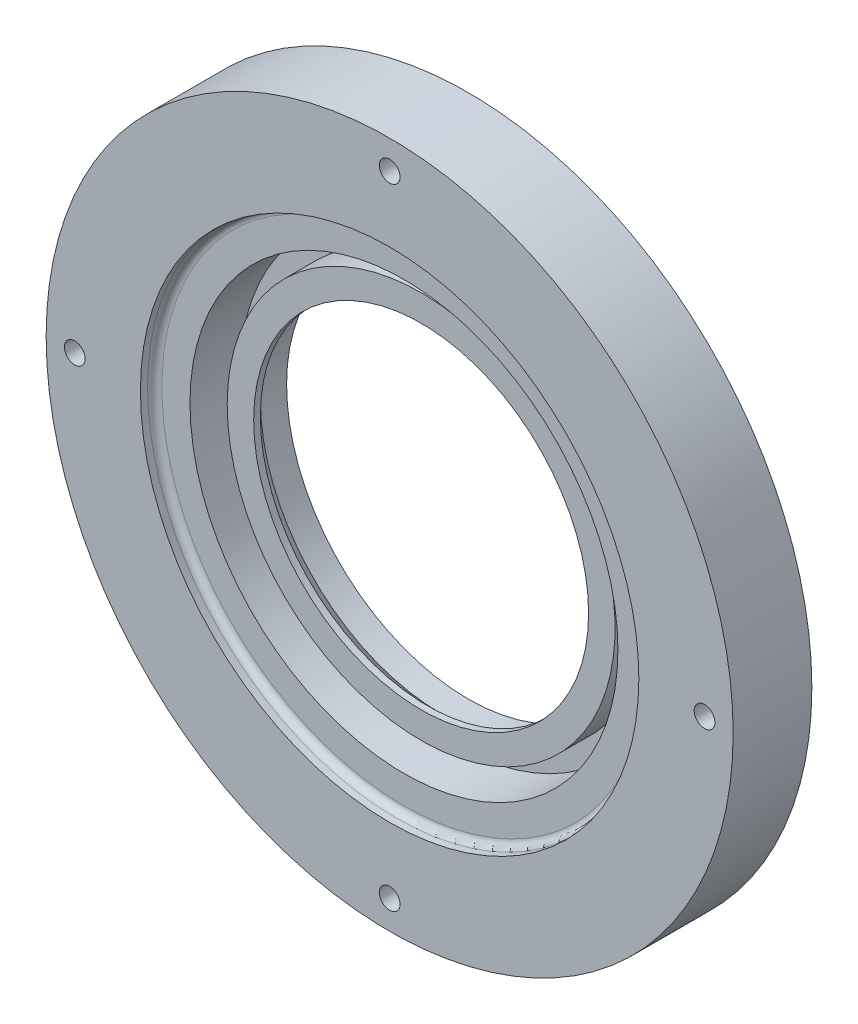
SolidWorks part; units mm, degrees
ref_plane "Front Plane" through (0, 0, 0) normal (0, 0, 1) x (1, 0, 0)
ref_plane "Top Plane" through (0, 0, 0) normal (0, 1, 0) x (1, 0, 0)
ref_plane "Right Plane" through (0, 0, 0) normal (1, 0, 0) x (0, 0, -1)
sketch "Sketch2" plane through (149.1164, 233.0393, -142.5293) normal (-0.6045, 0.7966, 0) x (0.7966, 0.6045, 0)
  line L0 (-23.4, 2.4) -> (-23.4, 3.3343)
  line L1 (-23.4, 3.3343) -> (-25.4, 5.3343)
  line L2 (-25.4, 5.3343) -> (-25.4, 9)
  line L3 (-25.4, 9) -> (-48, 9)
  line L17 (-27.1, 2.4) -> (-23.4, 2.4)
  line L18 (-34.825, 0) -> (-29.9, 0)
  line L19 (-23, 3.5) -> (-23, 2) construction
  line L20 (-29.9, 0) -> (-29.9, 7)
  line L21 (-29.5, 6.6) -> (-29.5, 0) construction
  line L25 (-25, 15) -> (-25, 5.5) construction
  line L26 (-25, 5.5) -> (-23, 3.5) construction
  line L27 (-27.1, 7) -> (-27.1, 2.4)
  line L28 (-27.5, 6.6) -> (-27.5, 2) construction
  line L30 (-27.1, 7) -> (-29.9, 7)
  line L32 (27.5, 2) -> (-27.5, 2) construction
  line L34 (29.5, 6.6) -> (-29.5, 6.6) construction
  line L36 (-29.5, 0) -> (29.5, 0) construction
  line L38 (-48, -2) -> (-34.825, -2)
  line L39 (-34.825, -2) -> (-34.825, 0)
  line L40 (-48, 9) -> (-48, -2)
  point P6 (-34.825, -1)
  dimension "D2" = 0.4
  dimension "D3" = 0.4
  dimension "D4" = 0.4
  dimension "D5" = 0.4
  dimension "D6" = 0.4
  dimension "D7" = 9
  dimension "D8" = 0.4
  dimension "D9" = 0.4
  dimension "D10" = 34.825
  dimension "D11" = 2
  dimension "D12" = 48
sketch "Sketch3" plane through (149.1164, 233.0393, -142.5293) normal (-0.6045, 0.7966, 0) x (0.7966, 0.6045, 0)
  line L0 (0, 13.4407) -> (0, -7.4209) construction
revolve "Revolve1" add sketch "Sketch2" angle 360 about L0
fillet "Fillet1" radius 1 1 edges at (114.2914, 233.0393, -142.5293)
hole_wizard "CBORE for M2.5 SHCS1" positions "Sketch10" profile "Sketch11" counterbore size "M2.5" standard "ANSI Metric"
sketch "Sketch10" plane through (0, 0, -151.5293) normal (0, 0, -1) x (-1, 0, 0)
  point P0 (-149.1164, 277.0393)
  point P2 (-149.1164, 189.0393)
  point P4 (-105.1164, 233.0393)
  point P6 (-193.1164, 233.0393)
  point P9 (0, 0)
  point P10 (0, 0)
  point P11 (0, 0)
  point P13 (0, 0)
  dimension "D1" = 44
  dimension "D2" = 44
  dimension "D3" = 88
  dimension "D4" = 88
sketch "Sketch11" plane through (149.1164, 277.0393, -151.5293) normal (1, 0, 0) x (0, 1, 0)
  line L0 (0, 0) -> (0, 11.8712)
  line L1 (0, 11.8712) -> (1.45, 11)
  line L2 (1.45, 11) -> (1.45, 5.5)
  line L3 (1.45, 5.5) -> (2.75, 5.5)
  line L4 (2.75, 5.5) -> (2.75, 0)
  line L5 (2.75, 0) -> (0, 0)
  line L10 (0, 11.8712) -> (-1.45, 11) construction
  line L11 (0, -6.35) -> (0, 107.95) construction
  dimension "Hole Dia." = 2.9
  dimension "Hole Depth" = 11
  dimension "C'Bore Dia." = 5.5
  dimension "C'Bore Depth" = 5.5
  dimension "Drill Angle" = 118
